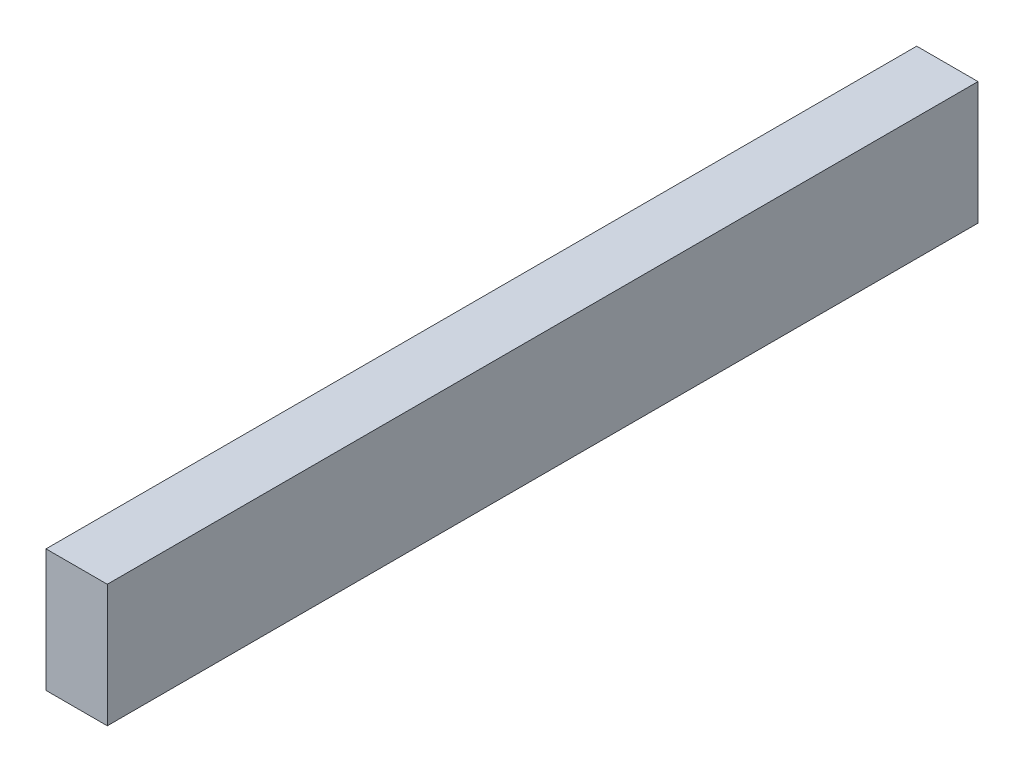
SolidWorks part; units mm, degrees
ref_plane "Front Plane" through (0, 0, 0) normal (0, 0, 1) x (1, 0, 0)
ref_plane "Top Plane" through (0, 0, 0) normal (0, 1, 0) x (1, 0, 0)
ref_plane "Right Plane" through (0, 0, 0) normal (1, 0, 0) x (0, 0, -1)
sketch "Sketch2" plane through (0, 0, 0) normal (0, 0, 1) x (1, 0, 0)
  line L1 (0, 0) -> (50.8, 0)
  line L2 (0, 0) -> (0, 101.6)
  line L3 (0, 101.6) -> (50.8, 101.6)
  line L4 (50.8, 0) -> (50.8, 101.6)
  dimension "D1" = 50.8
  dimension "D2" = 101.6
extrude "Boss-Extrude1" add sketch "Sketch2" along normal blind 721.45
